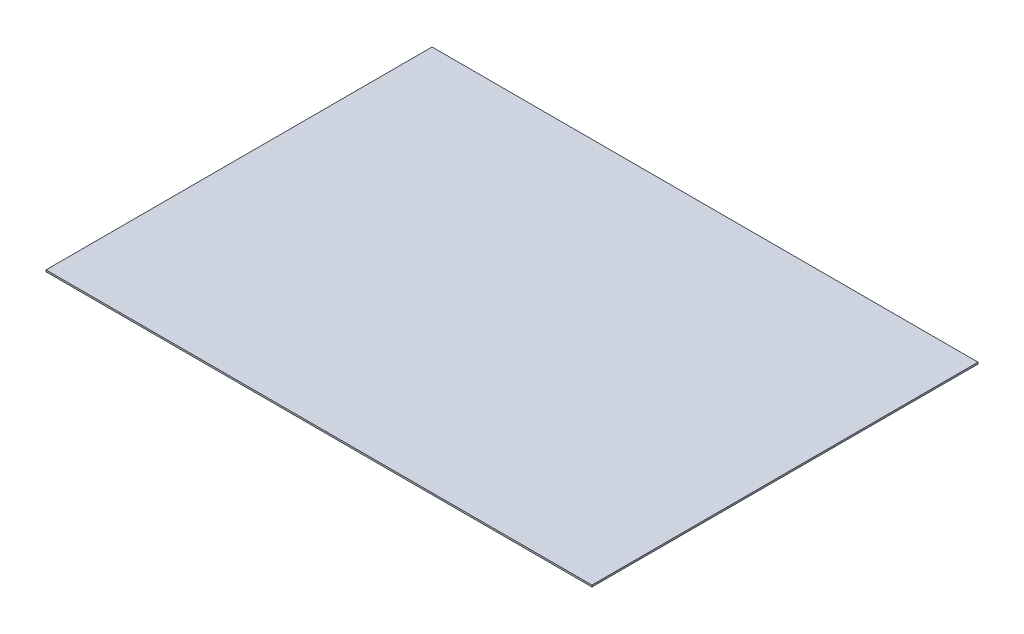
SolidWorks part; units mm, degrees
ref_plane "Front Plane" through (0, 0, 0) normal (0, 0, 1) x (1, 0, 0)
ref_plane "Top Plane" through (0, 0, 0) normal (0, 1, 0) x (1, 0, 0)
ref_plane "Right Plane" through (0, 0, 0) normal (1, 0, 0) x (0, 0, -1)
sketch "Sketch1" plane through (0, 0, 0) normal (0, 1, 0) x (1, 0, 0)
  line L1 (-210, 148.5) -> (210, 148.5)
  line L2 (-210, 148.5) -> (-210, -148.5)
  line L3 (-210, -148.5) -> (210, -148.5)
  line L4 (210, 148.5) -> (210, -148.5)
  line L5 (-210, 148.5) -> (210, -148.5) construction
  line L6 (-210, -148.5) -> (210, 148.5) construction
  point P0 (0, 0)
  dimension "D1" = 420
  dimension "D2" = 297
extrude "Boss-Extrude1" add sketch "Sketch1" along normal blind 1.3
sketch "Sketch2" plane through (0, 1.3, 0) normal (0, 1, 0) x (1, 0, 0)
  line L0 (-210, 148.5) -> (-210, -148.5) construction
  line L1 (-205, 143.5) -> (205, 143.5)
  line L2 (-205, 143.5) -> (-205, -143.5)
  line L3 (-205, -143.5) -> (205, -143.5)
  line L4 (205, 143.5) -> (205, -143.5)
  line L5 (-205, 143.5) -> (205, -143.5) construction
  line L6 (-205, -143.5) -> (205, 143.5) construction
  line L7 (210, 148.5) -> (-210, 148.5) construction
  point P0 (0, 0)
  dimension "D1" = 5
  dimension "D2" = 5
